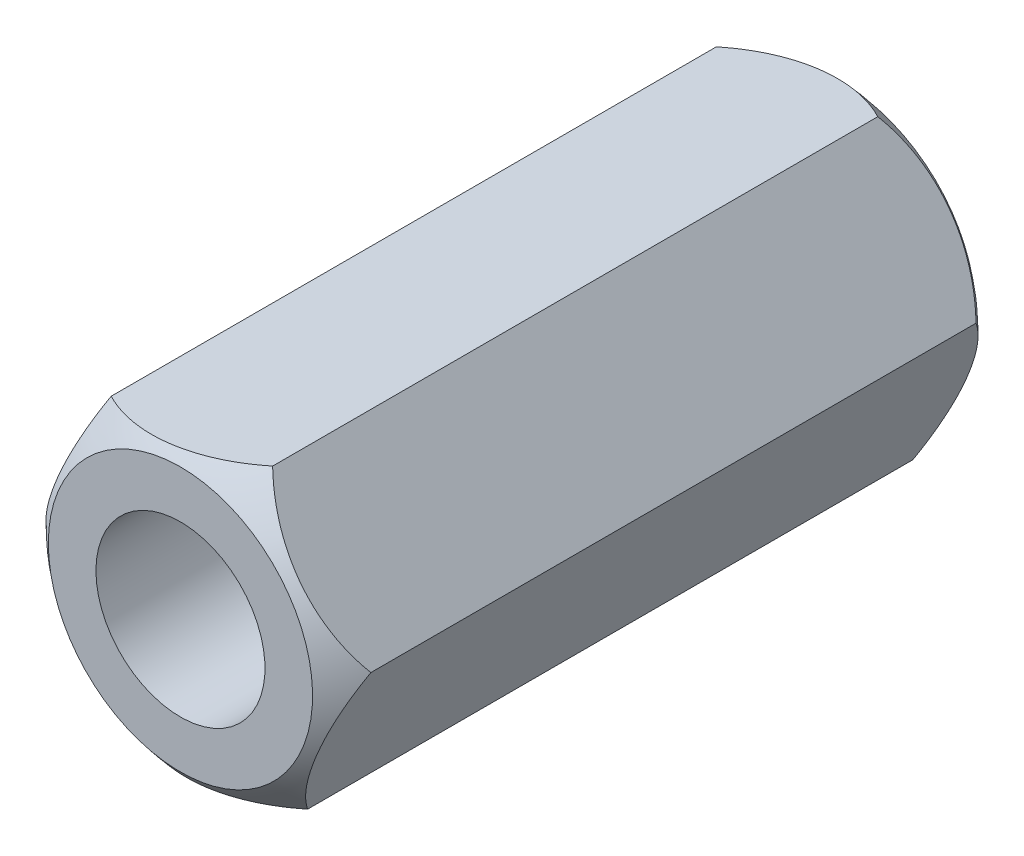
SolidWorks part; units mm, degrees
ref_plane "Plan de face" through (0, 0, 0) normal (0, 0, 1) x (1, 0, 0)
ref_plane "Plan de dessus" through (0, 0, 0) normal (0, 1, 0) x (1, 0, 0)
ref_plane "Plan de droite" through (0, 0, 0) normal (1, 0, 0) x (0, 0, -1)
sketch "Esquisse1" plane through (0, 0, 0) normal (0, 0, 1) x (1, 0, 0)
  line L1 (3.8131, 9.044) -> (-5.9257, 7.8243)
  line L2 (-5.9257, 7.8243) -> (-9.7389, -1.2197)
  line L3 (-9.7389, -1.2197) -> (-3.8131, -9.044)
  line L4 (-3.8131, -9.044) -> (5.9257, -7.8243)
  line L5 (5.9257, -7.8243) -> (9.7389, 1.2197)
  line L6 (9.7389, 1.2197) -> (3.8131, 9.044)
  circle A0 centre (0, 0) radius 8.5 construction
  dimension "D1" = 17
extrude "Extrusion1" add sketch "Esquisse1" along normal blind 40
hole_wizard "Trou taraudé M121" positions "Esquisse4" profile "Esquisse3" tap size "M12" standard "ISO" end condition through all
sketch "Esquisse4" plane through (0, 0, 0) normal (0, 0, -1) x (-1, 0, 0)
  point P0 (0, 0)
sketch "Esquisse3" plane through (0, 0, 0) normal (1, 0, 0) x (0, 1, 0)
  line L0 (0, 0) -> (0, 40)
  line L1 (0, 40) -> (5.1, 40)
  line L2 (5.1, 40) -> (5.1, 0)
  line L5 (5.1, 0) -> (0, 0)
  line L11 (0, -6.35) -> (0, 107.95) construction
  dimension "Diamètre du trou pour taraudage jusqu'au prochain" = 10.2
  dimension "Profondeur du trou pour taraudage jusqu'au prochain" = 40
cosmetic thread "Filetage de perçage1" parameters "D2"=12
sketch "Esquisse5" plane through (0, 0, 0) normal (0, 1, 0) x (1, 0, 0)
  line L0 (0, 7.3893) -> (0, 2.7312)
  line L1 (0, 7.3893) -> (12.9938, 7.3893)
  line L2 (12.9938, 7.3893) -> (12.9938, -10.2626)
  line L3 (0, -10.2626) -> (0, 11.3226) construction
  line L4 (0, -20) -> (19.0795, -20) construction
  line L5 (12.9938, -47.3893) -> (12.9938, -29.7374)
  line L6 (0, -47.3893) -> (12.9938, -47.3893)
  line L7 (0, -47.3893) -> (0, -42.7312)
  arc A0 (12.9938, -10.2626) -> (0, 2.7312) centre (0, -10.2626) ccw
  arc A1 (12.9938, -29.7374) -> (0, -42.7312) centre (0, -29.7374) cw
revolve "Enlèvement de matière-Révolution1" cut sketch "Esquisse5" angle 360 about L3
